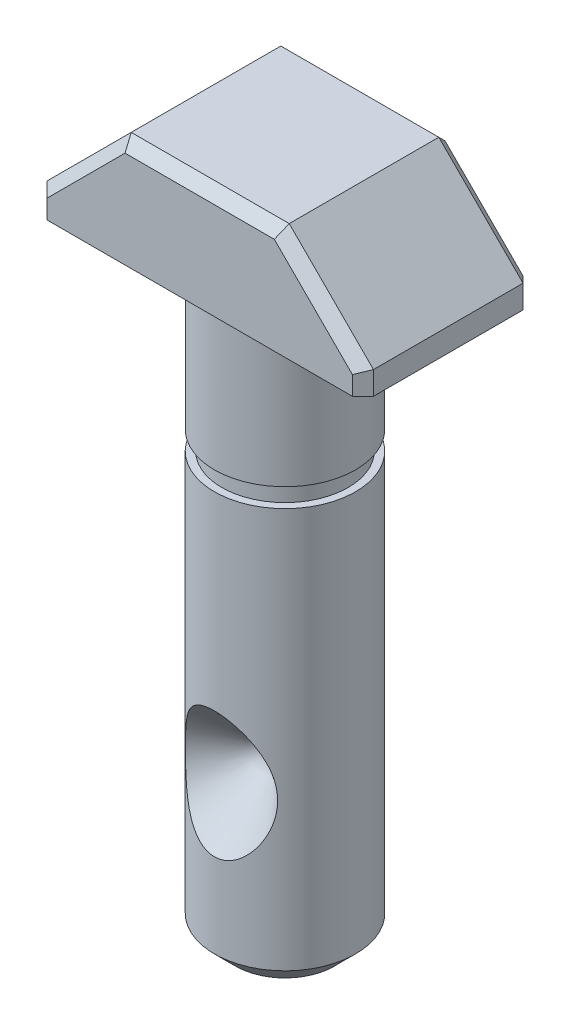
SolidWorks part; units mm, degrees
ref_plane "前视基准面" through (0, 0, 0) normal (0, 0, 1) x (1, 0, 0)
ref_plane "上视基准面" through (0, 0, 0) normal (0, 1, 0) x (1, 0, 0)
ref_plane "右视基准面" through (0, 0, 0) normal (1, 0, 0) x (0, 0, -1)
sketch "草图1" plane through (0, 0, 0) normal (0, 0, 1) x (1, 0, 0)
  line L1 (-7.75, -2.55) -> (7.75, -2.55)
  line L2 (-7.75, -2.55) -> (-7.75, 2.55)
  line L3 (-7.75, 2.55) -> (7.75, 2.55)
  line L4 (7.75, -2.55) -> (7.75, 2.55)
  line L5 (-7.75, -2.55) -> (7.75, 2.55) construction
  line L6 (-7.75, 2.55) -> (7.75, -2.55) construction
  point P0 (0, 0)
  dimension "D1" = 15.5
  dimension "D2" = 5.1
extrude "凸台-拉伸1" add sketch "草图1" along normal blind 8.1
chamfer "倒角1" distance 4 angle 45 2 edges at (7.75, 2.55, 4.05) (-7.75, 2.55, 4.05)
chamfer "倒角2" distance 0.5 angle 45 10 edges at (-7.75, -2, 0) (-5.75, 0.55, 0) (0, 2.55, 0) (5.75, 0.55, 0) (7.75, -2, 0) (7.75, -2, 8.1) (5.75, 0.55, 8.1) (0, 2.55, 8.1) (-5.75, 0.55, 8.1) (-7.75, -2, 8.1)
sketch "草图2" plane through (0, -2.55, 0) normal (0, -1, 0) x (1, 0, 0)
  line L0 (-7.25, 0) -> (7.25, 0) construction
  circle A0 centre (0, 4.05) radius 3.35
  dimension "D1" = 6.7
  dimension "D2" = 4.05
extrude "凸台-拉伸2" add sketch "草图2" along normal blind 7
sketch "草图3" plane through (0, -9.55, 0) normal (0, -1, 0) x (1, 0, 0)
  circle A0 centre (0, 4.05) radius 3
  dimension "D1" = 6
extrude "凸台-拉伸3" add sketch "草图3" along normal blind 0.9
sketch "草图5" plane through (0, -10.45, 0) normal (0, -1, 0) x (1, 0, 0)
  circle A0 centre (0, 4.05) radius 3.35
  dimension "D1" = 6.7
extrude "凸台-拉伸4" add sketch "草图5" along normal blind 20
chamfer "倒角3" distance 1 angle 45 1 edges at (0, -30.45, 0.7)
sketch "草图6" plane through (0, 0, 0) normal (1, 0, 0) x (0, 0, -1)
  line L0 (-7.4, -22.4551) -> (-7.4, -19.4551)
  line L1 (-7.4, -10.45) -> (-7.4, -29.45) construction
  line L2 (-7.4, -22.4551) -> (-4.4, -22.4551)
  line L3 (-7.4, -19.4551) -> (-4.4, -22.4551)
  dimension "D1" = 3
  dimension "D2" = 3
revolve "切除-旋转1" cut sketch "草图6" angle 360 about L2
